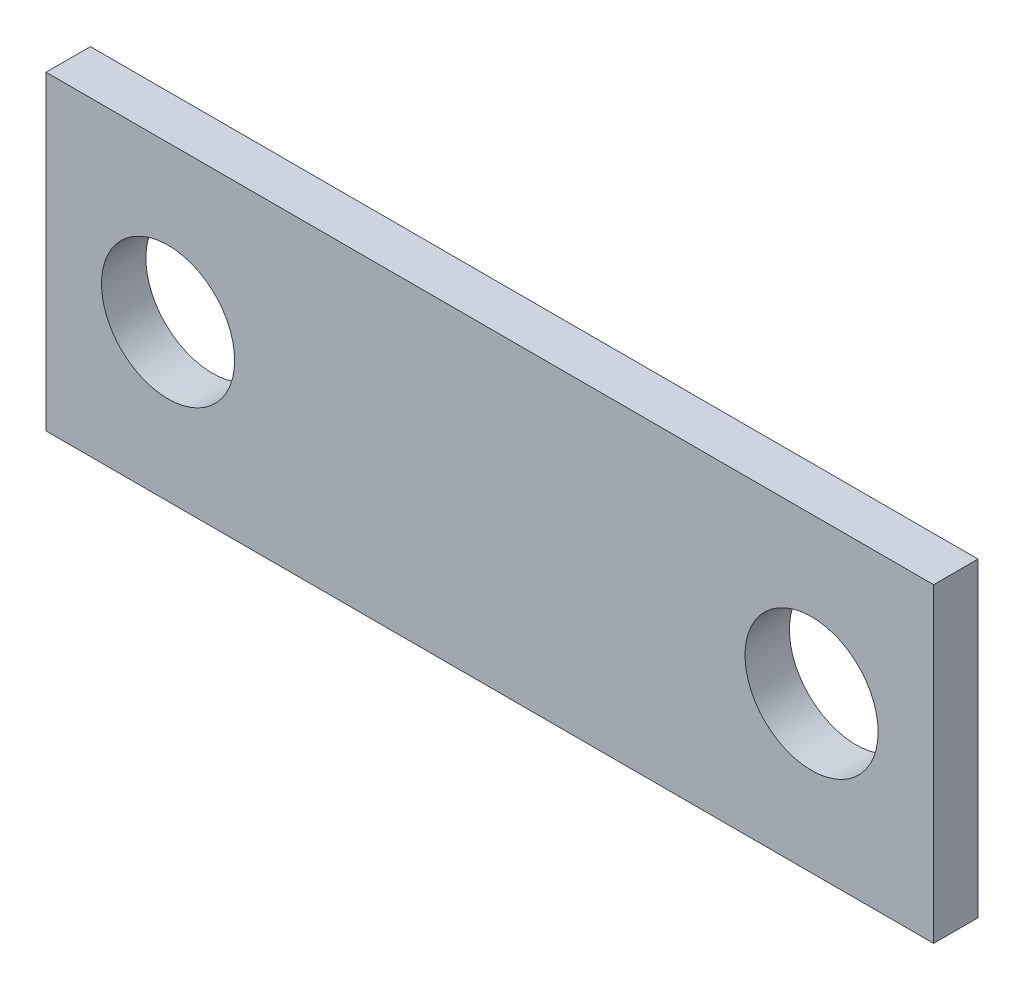
SolidWorks part; units mm, degrees
ref_plane "Front Plane" through (0, 0, 0) normal (0, 0, 1) x (1, 0, 0)
ref_plane "Top Plane" through (0, 0, 0) normal (0, 1, 0) x (1, 0, 0)
ref_plane "Right Plane" through (0, 0, 0) normal (1, 0, 0) x (0, 0, -1)
sketch "Sketch1" plane through (0, 0, 0) normal (0, 0, 1) x (1, 0, 0)
  line L1 (10, -3.5) -> (-10, -3.5)
  line L2 (10, -3.5) -> (10, 3.5)
  line L3 (10, 3.5) -> (-10, 3.5)
  line L4 (-10, -3.5) -> (-10, 3.5)
  line L5 (10, -3.5) -> (-10, 3.5) construction
  line L6 (10, 3.5) -> (-10, -3.5) construction
  point P0 (0, 0)
  dimension "D1" = 20
  dimension "D2" = 7
extrude "Boss-Extrude1" add sketch "Sketch1" along normal blind 1
sketch "Sketch2" plane through (0, 0, 1) normal (0, 0, 1) x (1, 0, 0)
  circle A0 centre (-7.25, 0) radius 1.5
  circle A1 centre (7.25, 0) radius 1.5
  dimension "D3" = 3
  dimension "D4" = 3
  dimension "D1" = 14.5
  dimension "D2" = 7.25
extrude "Cut-Extrude1" cut sketch "Sketch2" against normal blind 1
